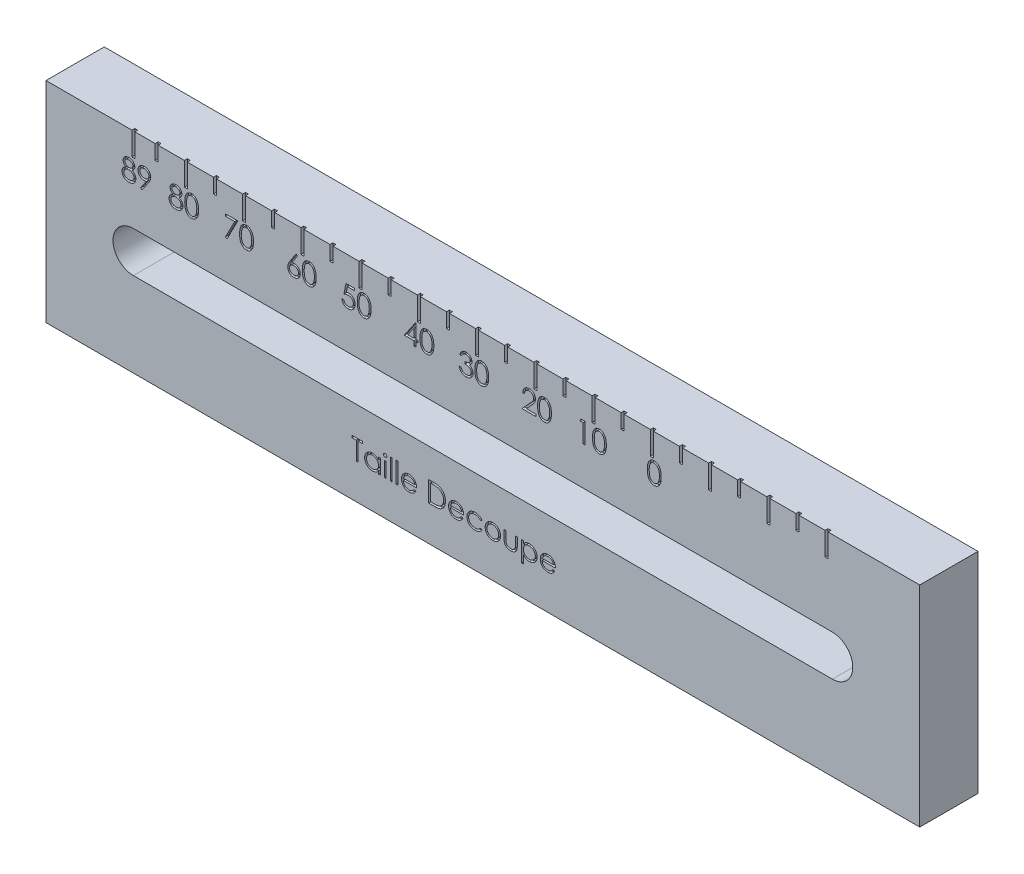
SolidWorks part; units mm, degrees
ref_plane "Plan de face" through (0, 0, 0) normal (0, 0, 1) x (1, 0, 0)
ref_plane "Plan de dessus" through (0, 0, 0) normal (0, 1, 0) x (1, 0, 0)
ref_plane "Plan de droite" through (0, 0, 0) normal (1, 0, 0) x (0, 0, -1)
sketch "Esquisse1" plane through (0, 0, 0) normal (0, 0, 1) x (1, 0, 0)
  line L0 (-162.8354, 18) -> (20.962, 18) construction
  line L1 (0, 0) -> (-150, 0)
  line L2 (0, 0) -> (0, 36)
  line L3 (0, 36) -> (-150, 36)
  line L4 (-150, 0) -> (-150, 36)
  line L5 (-135, 18) -> (-15, 18) construction
  line L6 (-135, 21.5) -> (-15, 21.5)
  line L7 (-135, 14.5) -> (-15, 14.5)
  arc A0 (-135, 21.5) -> (-135, 14.5) centre (-135, 18) ccw
  arc A1 (-15, 14.5) -> (-15, 21.5) centre (-15, 18) ccw
  point P7 (0, 18)
  point P10 (-75, 18)
  dimension "D1" = 36
  dimension "D2" = 150
  dimension "D3" = 7
  dimension "D4" = 15
  dimension "D5" = 15
extrude "Boss.-Extru.1" add sketch "Esquisse1" along normal blind 10
sketch "Esquisse2" plane through (0, 0, 10) normal (0, 0, 1) x (1, 0, 0)
  line L0 (-135, -4.6947) -> (-135, 43.6081) construction
  line L1 (0, 36) -> (-150, 36) construction
  line L2 (-135.25, 36) -> (-134.75, 36)
  line L3 (-135.25, 36) -> (-135.25, 32.0149)
  line L4 (-135.25, 32.0149) -> (-134.75, 32.0149)
  line L5 (-134.75, 36) -> (-134.75, 32.0149)
  line L6 (-137.086, 28.0881) -> (-7.3015, 28.0881) construction
  line L7 (-126, 39.0798) -> (-126, 23.7347) construction
  line L8 (-115.75, 36) -> (-115.75, 32.0149)
  line L9 (-126.25, 36) -> (-125.75, 36)
  line L10 (-126.25, 36) -> (-126.25, 32.0149)
  line L11 (-126.25, 32.0149) -> (-125.75, 32.0149)
  line L12 (-125.75, 36) -> (-125.75, 32.0149)
  line L13 (-116.25, 36) -> (-115.75, 36)
  line L14 (-116.25, 36) -> (-116.25, 32.0149)
  line L15 (-116.25, 32.0149) -> (-115.75, 32.0149)
  line L16 (-105.75, 36) -> (-105.75, 32.0149)
  line L17 (-106.25, 36) -> (-105.75, 36)
  line L18 (-106.25, 36) -> (-106.25, 32.0149)
  line L19 (-106.25, 32.0149) -> (-105.75, 32.0149)
  line L20 (-95.75, 36) -> (-95.75, 32.0149)
  line L21 (-96.25, 36) -> (-95.75, 36)
  line L22 (-96.25, 36) -> (-96.25, 32.0149)
  line L23 (-96.25, 32.0149) -> (-95.75, 32.0149)
  line L24 (-85.75, 36) -> (-85.75, 32.0149)
  line L25 (-86.25, 36) -> (-85.75, 36)
  line L26 (-86.25, 36) -> (-86.25, 32.0149)
  line L27 (-86.25, 32.0149) -> (-85.75, 32.0149)
  line L28 (-75.75, 36) -> (-75.75, 32.0149)
  line L29 (-76.25, 36) -> (-75.75, 36)
  line L30 (-76.25, 36) -> (-76.25, 32.0149)
  line L31 (-76.25, 32.0149) -> (-75.75, 32.0149)
  line L32 (-65.75, 36) -> (-65.75, 32.0149)
  line L33 (-66.25, 36) -> (-65.75, 36)
  line L34 (-66.25, 36) -> (-66.25, 32.0149)
  line L35 (-66.25, 32.0149) -> (-65.75, 32.0149)
  line L36 (-55.75, 36) -> (-55.75, 32.0149)
  line L37 (-56.25, 36) -> (-55.75, 36)
  line L38 (-56.25, 36) -> (-56.25, 32.0149)
  line L39 (-56.25, 32.0149) -> (-55.75, 32.0149)
  line L40 (-45.75, 36) -> (-45.75, 32.0149)
  line L41 (-46.25, 36) -> (-45.75, 36)
  line L42 (-46.25, 36) -> (-46.25, 32.0149)
  line L43 (-46.25, 32.0149) -> (-45.75, 32.0149)
  line L44 (-35.75, 36) -> (-35.75, 32.0149)
  line L45 (-36.25, 36) -> (-35.75, 36)
  line L46 (-36.25, 36) -> (-36.25, 32.0149)
  line L47 (-36.25, 32.0149) -> (-35.75, 32.0149)
  line L48 (-25.75, 36) -> (-25.75, 32.0149)
  line L49 (-26.25, 36) -> (-25.75, 36)
  line L50 (-26.25, 36) -> (-26.25, 32.0149)
  line L51 (-26.25, 32.0149) -> (-25.75, 32.0149)
  line L52 (-15.75, 36) -> (-15.75, 32.0149)
  line L53 (-16.25, 36) -> (-15.75, 36)
  line L54 (-16.25, 36) -> (-16.25, 32.0149)
  line L55 (-16.25, 32.0149) -> (-15.75, 32.0149)
  line L56 (-102.9218, 6.0238) -> (63.4049, 6.0238) construction
  line L57 (-46, 41.0226) -> (-46, -10.2252) construction
  line L58 (0, 36) -> (-150, 36) construction
  line L59 (-131.25, 36) -> (-130.75, 36)
  line L60 (-131.25, 36) -> (-131.25, 33.5)
  line L61 (-131.25, 33.5) -> (-130.75, 33.5)
  line L62 (-130.75, 36) -> (-130.75, 33.5)
  line L63 (-120.75, 36) -> (-120.75, 33.5)
  line L64 (-121.25, 33.5) -> (-120.75, 33.5)
  line L65 (-121.25, 36) -> (-121.25, 33.5)
  line L66 (-121.25, 36) -> (-120.75, 36)
  line L67 (-110.75, 36) -> (-110.75, 33.5)
  line L68 (-111.25, 33.5) -> (-110.75, 33.5)
  line L69 (-111.25, 36) -> (-111.25, 33.5)
  line L70 (-111.25, 36) -> (-110.75, 36)
  line L71 (-100.75, 36) -> (-100.75, 33.5)
  line L72 (-101.25, 33.5) -> (-100.75, 33.5)
  line L73 (-101.25, 36) -> (-101.25, 33.5)
  line L74 (-101.25, 36) -> (-100.75, 36)
  line L75 (-90.75, 36) -> (-90.75, 33.5)
  line L76 (-91.25, 33.5) -> (-90.75, 33.5)
  line L77 (-91.25, 36) -> (-91.25, 33.5)
  line L78 (-91.25, 36) -> (-90.75, 36)
  line L79 (-80.75, 36) -> (-80.75, 33.5)
  line L80 (-81.25, 33.5) -> (-80.75, 33.5)
  line L81 (-81.25, 36) -> (-81.25, 33.5)
  line L82 (-81.25, 36) -> (-80.75, 36)
  line L83 (-70.75, 36) -> (-70.75, 33.5)
  line L84 (-71.25, 33.5) -> (-70.75, 33.5)
  line L85 (-71.25, 36) -> (-71.25, 33.5)
  line L86 (-71.25, 36) -> (-70.75, 36)
  line L87 (-60.75, 36) -> (-60.75, 33.5)
  line L88 (-61.25, 33.5) -> (-60.75, 33.5)
  line L89 (-61.25, 36) -> (-61.25, 33.5)
  line L90 (-61.25, 36) -> (-60.75, 36)
  line L91 (-50.75, 36) -> (-50.75, 33.5)
  line L92 (-51.25, 33.5) -> (-50.75, 33.5)
  line L93 (-51.25, 36) -> (-51.25, 33.5)
  line L94 (-51.25, 36) -> (-50.75, 36)
  line L95 (-40.75, 36) -> (-40.75, 33.5)
  line L96 (-41.25, 33.5) -> (-40.75, 33.5)
  line L97 (-41.25, 36) -> (-41.25, 33.5)
  line L98 (-41.25, 36) -> (-40.75, 36)
  line L99 (-30.75, 36) -> (-30.75, 33.5)
  line L100 (-31.25, 33.5) -> (-30.75, 33.5)
  line L101 (-31.25, 36) -> (-31.25, 33.5)
  line L102 (-31.25, 36) -> (-30.75, 36)
  line L103 (-20.75, 36) -> (-20.75, 33.5)
  line L104 (-21.25, 33.5) -> (-20.75, 33.5)
  line L105 (-21.25, 36) -> (-21.25, 33.5)
  line L106 (-21.25, 36) -> (-20.75, 36)
  text T0 "89  80   70    60   50    40   30    20   10     0"
  text T1 "    Taille Decoupe"
  point P9 (-135, 32.0149)
  point P19 (-126, 32.0149)
  dimension "D1" = 0.5
  dimension "D2" = 9
  dimension "D3" = 0.5
  dimension "D5" = 0.5
  dimension "D6" = 2.5
  dimension "D7" = 4.5
  dimension "D4" = 12
  dimension "D8" = 12
extrude "Enlèv. mat.-Extru.1" cut sketch "Esquisse2" against normal blind 0.5
